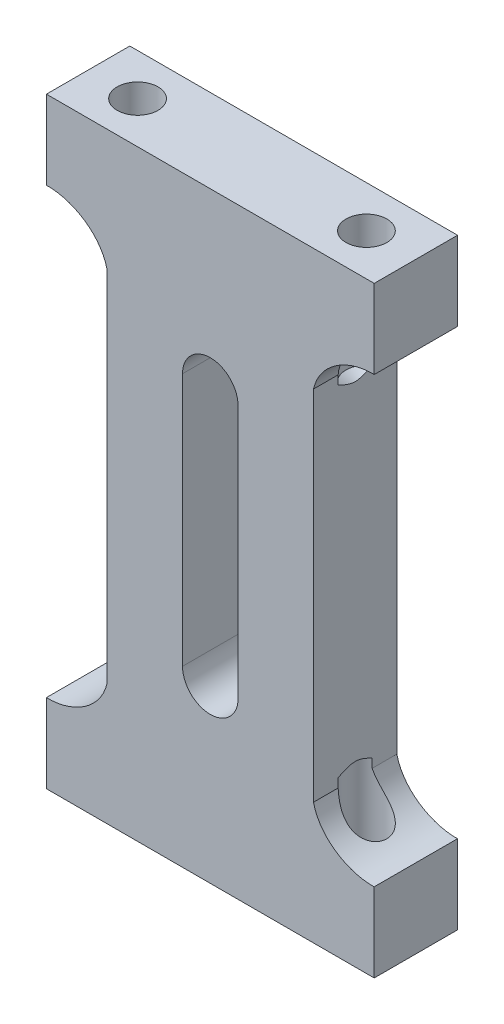
SolidWorks part; units mm, degrees
ref_plane "Piano frontale" through (0, 0, 0) normal (0, 0, 1) x (1, 0, 0)
ref_plane "Piano superiore" through (0, 0, 0) normal (0, 1, 0) x (1, 0, 0)
ref_plane "Piano destro" through (0, 0, 0) normal (1, 0, 0) x (0, 0, -1)
sketch "Schizzo1" plane through (0, 0, 0) normal (0, 0, 1) x (1, 0, 0)
  line L0 (27.6289, 43.033) -> (27.6289, 27.533) construction
  line L1 (17.6039, 53.683) -> (37.6539, 53.683)
  line L2 (17.6039, 53.683) -> (17.6039, 16.883)
  line L3 (17.6039, 16.883) -> (37.6539, 16.883)
  line L4 (37.6539, 53.683) -> (37.6539, 16.883)
  line L5 (29.3289, 43.033) -> (29.3289, 27.533)
  line L6 (25.9289, 43.033) -> (25.9289, 27.533)
  line L7 (27.6289, 53.683) -> (27.6289, 16.883) construction
  line L8 (21.3174, 46.2274) -> (21.3174, 24.2781)
  line L9 (17.6039, 35.283) -> (37.6539, 35.283) construction
  line L10 (33.9405, 46.2274) -> (33.9405, 24.2781)
  arc A0 (29.3289, 43.033) -> (25.9289, 43.033) centre (27.6289, 43.033) ccw
  arc A1 (25.9289, 27.533) -> (29.3289, 27.533) centre (27.6289, 27.533) ccw
  spline S0 degree 3 poles (21.3174, 46.2274) (20.9521, 47.8459) (19.2074, 48.899) (17.6039, 48.8515) knots 0 0 0 0 1 1 1 1
  spline S1 degree 3 poles (21.3174, 24.3387) (20.9521, 22.7201) (19.2074, 21.667) (17.6039, 21.7145) knots 0 0 0 0 1 1 1 1
  spline S2 degree 3 poles (33.9405, 24.3387) (34.3058, 22.7201) (36.0505, 21.667) (37.6539, 21.7145) knots 0 0 0 0 1 1 1 1
  spline S3 degree 3 poles (33.9405, 46.2274) (34.3058, 47.8459) (36.0505, 48.899) (37.6539, 48.8515) knots 0 0 0 0 1 1 1 1
  point P6 (27.6289, 35.283)
  dimension "D1" = 20.05
  dimension "D2" = 36.8
  dimension "D3" = 3.4
  dimension "D4" = 15.5
extrude "Estrusione-Estrusione1" add sketch "Schizzo1" along normal blind 5.1
hole_wizard "Foro filettato M3x0.5-1" positions "Schizzo3" profile "Schizzo2" tap size "M3x0.5" standard "Ansi Metric"
sketch "Schizzo3" plane through (0, 53.683, 0) normal (0, 1, 0) x (1, 0, 0)
  line L0 (20.6289, -2.55) -> (34.6289, -2.55) construction
  line L1 (27.6289, -5.1) -> (27.6289, 0) construction
  line L2 (17.6039, -5.1) -> (37.6539, -5.1) construction
  line L3 (17.6039, 0) -> (37.6539, 0) construction
  point P0 (20.6289, -2.55)
  point P2 (34.6289, -2.55)
  point P15 (27.6289, -2.55)
  dimension "D1" = 14
sketch "Schizzo2" plane through (20.6289, 53.683, 2.55) normal (1, 0, 0) x (0, 0, 1)
  line L0 (0, 0) -> (0, 8.7511)
  line L1 (0, 8.7511) -> (1.25, 8)
  line L2 (1.25, 8) -> (1.25, 0)
  line L5 (1.25, 0) -> (0, 0)
  line L10 (0, 8.7511) -> (-1.25, 8) construction
  line L11 (0, -6.35) -> (0, 107.95) construction
  dimension "Tap Drill Dia." = 2.5
  dimension "Tap Drill Depth" = 8
  dimension "Drill Angle" = 118
cosmetic thread "Filettatura del foro1" parameters "D1"=8, "D2"=3
cosmetic thread "Filettatura del foro2" parameters "D1"=8, "D2"=3
ref_plane "Piano1" through (0, 35.283, 0) normal (0, 1, 0) x (1, 0, 0)
mirror "Specchia1" about plane through (0, 35.283, 0) normal (0, 1, 0) of "Foro filettato M3x0.5-1"
